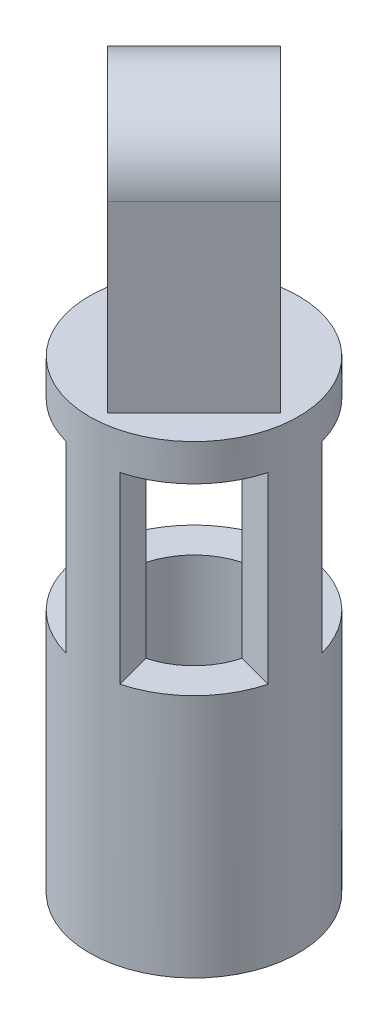
SolidWorks part; units mm, degrees
ref_plane "Спереди" through (0, 0, 0) normal (0, 0, 1) x (1, 0, 0)
ref_plane "Сверху" through (0, 0, 0) normal (0, 1, 0) x (1, 0, 0)
ref_plane "Справа" through (0, 0, 0) normal (1, 0, 0) x (0, 0, -1)
other "Configuration Table"
sketch "Эскиз4" plane through (0, 0, 0) normal (0, 1, 0) x (1, 0, 0)
  circle A0 centre (0, 0) radius 8.55
  circle A1 centre (0, 0) radius 5.55
  dimension "D1" = 11.1
  dimension "D2" = 3
extrude "Бобышка-Вытянуть1" add sketch "Эскиз4" along normal blind 20
sketch "Эскиз5" plane through (0, 20, 0) normal (0, 1, 0) x (1, 0, 0)
  line L0 (-1000, 0) -> (49000, 0) construction
  line L1 (0, -1000) -> (0, 49000) construction
  line L2 (0, 0) -> (1.4364, 5.3609) construction
  line L3 (1.4364, 5.3609) -> (2.2129, 8.2587) construction
  line L4 (2.2129, 8.2587) -> (1.4364, 5.3609)
  line L5 (-1.4364, 5.3609) -> (-2.2129, 8.2587) construction
  line L6 (-2.2129, 8.2587) -> (-1.4364, 5.3609)
  line L7 (8.2587, -2.2129) -> (5.3609, -1.4364)
  line L8 (8.2587, 2.2129) -> (5.3609, 1.4364)
  line L9 (-2.2129, -8.2587) -> (-1.4364, -5.3609)
  line L10 (2.2129, -8.2587) -> (1.4364, -5.3609)
  line L11 (-8.2587, 2.2129) -> (-5.3609, 1.4364)
  line L12 (-8.2587, -2.2129) -> (-5.3609, -1.4364)
  arc A1 (-1.4364, 5.3609) -> (1.4364, 5.3609) centre (0, 0) cw
  circle A4 centre (0, 0) radius 8.55 construction
  arc A5 (-2.2129, 8.2587) -> (2.2129, 8.2587) centre (0, 0) cw
  circle A8 centre (0, 0) radius 5.55 construction
  arc A9 (5.3609, 1.4364) -> (5.3609, -1.4364) centre (0, 0) cw
  arc A10 (8.2587, 2.2129) -> (8.2587, -2.2129) centre (0, 0) cw
  arc A11 (1.4364, -5.3609) -> (-1.4364, -5.3609) centre (0, 0) cw
  arc A12 (2.2129, -8.2587) -> (-2.2129, -8.2587) centre (0, 0) cw
  arc A13 (-5.3609, -1.4364) -> (-5.3609, 1.4364) centre (0, 0) cw
  arc A14 (-8.2587, -2.2129) -> (-8.2587, 2.2129) centre (0, 0) cw
  point P33 (0, 0)
  dimension "D1" = 15
  dimension "D2" = 4
extrude "Бобышка-Вытянуть2" add sketch "Эскиз5" along normal blind 15
sketch "Эскиз6" plane through (0, 35, 0) normal (0, 1, 0) x (1, 0, 0)
  circle A0 centre (0, 0) radius 8.55
  arc A3 (-8.2587, -2.2129) -> (-2.2129, -8.2587) centre (0, 0) ccw construction
extrude "Бобышка-Вытянуть3" add sketch "Эскиз6" along normal blind 3
ref_plane "Плоскость диагональная" through (0, 0, 0) normal (-0.7071, 0, 0.7071) x (0.7071, 0, 0.7071)
sketch "Эскиз9" plane through (0, 0, 0) normal (-0.7071, 0, 0.7071) x (0.7071, 0, 0.7071)
  line L0 (-5.7, 38) -> (-5.7, 53)
  line L1 (5.7, 53) -> (5.7, 38)
  line L3 (-5.7, 38) -> (0, 38)
  line L4 (8.55, 38) -> (-8.55, 38) construction
  line L6 (0, -1000) -> (0, 49000) construction
  line L7 (0, 38) -> (5.7, 38)
  arc A0 (-5.7, 53) -> (5.7, 53) centre (0, 53) cw
  circle A1 centre (0, 53) radius 2
  dimension "D2" = 4
  dimension "D1" = 15
  dimension "D3" = 11.4
extrude "Бобышка-Вытянуть4" add sketch "Эскиз9" along normal mid plane 10
